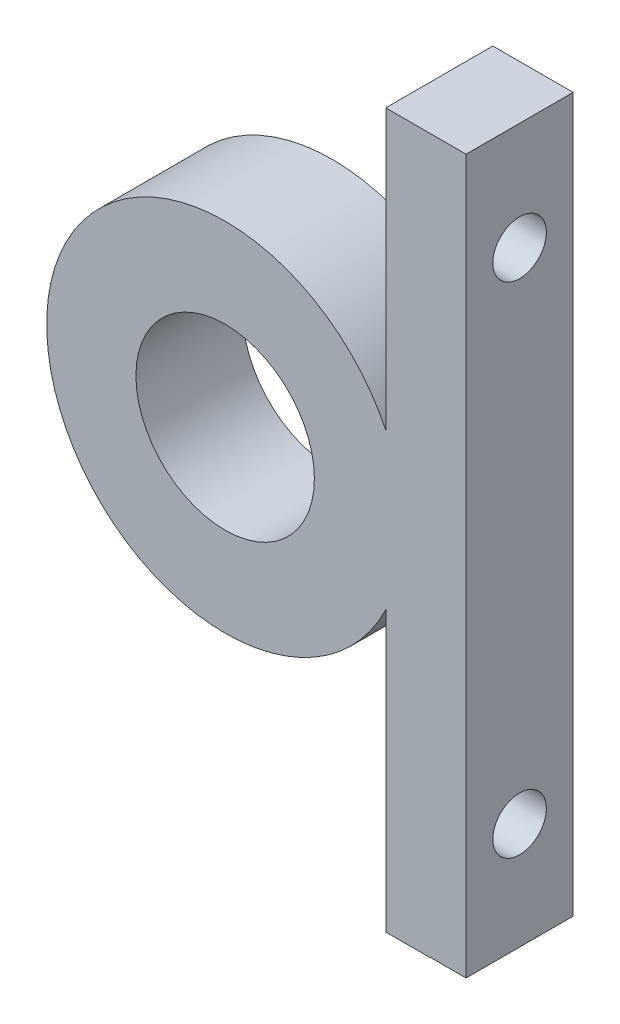
SolidWorks part; units mm, degrees
ref_plane "Front Plane" through (0, 0, 0) normal (0, 0, 1) x (1, 0, 0)
ref_plane "Top Plane" through (0, 0, 0) normal (0, 1, 0) x (1, 0, 0)
ref_plane "Right Plane" through (0, 0, 0) normal (1, 0, 0) x (0, 0, -1)
sketch "Sketch1" plane through (0, 0, 0) normal (0, 0, 1) x (1, 0, 0)
  line L0 (0, 22.784) -> (0, -28.016)
  line L1 (0, -28.016) -> (3.175, -28.016)
  line L2 (3.175, -28.016) -> (3.175, 22.784)
  line L3 (3.175, 22.784) -> (0, 22.784)
  line L4 (-11.43, -2.616) -> (3.175, -2.616) construction
  circle A0 centre (-11.43, -2.616) radius 12.7
  circle A1 centre (-11.43, -2.616) radius 6.35
  point P9 (3.175, -2.616)
  dimension "D2" = 12.7
  dimension "D3" = 25.4
  dimension "D1" = 3.175
  dimension "D4" = 14.605
  dimension "D5" = 50.8
  dimension "D6" = 25.4
extrude "Boss-Extrude1" add sketch "Sketch1" along normal blind 7.62 contours L0 A0 A1 | A0 L0 L1 L2 L3 | L0 A0 | L4 L0 A0 | L4 A0 L0 L1 L2
ref_plane "Plane1" through (5.715, 0, 0) normal (1, 0, 0) x (0, 0, -1)
sketch "Sketch3" plane through (5.715, 0, 0) normal (1, 0, 0) x (0, 0, -1)
  line L0 (-3.81, 22.784) -> (-3.81, -28.016) construction
  line L1 (-7.62, 22.784) -> (0, 22.784) construction
  line L2 (-7.62, -28.016) -> (0, -28.016) construction
  line L3 (-3.81, -28.016) -> (-3.81, -20.396)
  line L4 (-3.81, 22.784) -> (-3.81, 15.1167)
  circle A0 centre (-3.81, 15.1167) radius 1.905
  circle A1 centre (-3.81, -20.396) radius 1.905
  dimension "D1" = 3.81
  dimension "D2" = 3.81
extrude "Cut-Extrude1" cut sketch "Sketch3" against normal blind 10.16 and the other way blind 7.62 contours L0 L4 A0 | L4 L0 A0 | L0 A1 L3 | A1 L0 L3
sketch "Sketch4" plane through (0, 0, 7.62) normal (0, 0, 1) x (1, 0, 0)
  line L1 (3.175, 22.784) -> (5.715, 22.784)
  line L2 (3.175, 22.784) -> (3.175, -27.9921)
  line L3 (3.175, -27.9921) -> (5.715, -27.9921)
  line L4 (5.715, 22.784) -> (5.715, -27.9921)
  dimension "D1" = 2.54
extrude "Boss-Extrude2" add sketch "Sketch4" against normal blind 7.62
sketch "Sketch5" plane through (5.715, 0, 0) normal (1, 0, 0) x (0, 0, -1)
  circle A0 centre (-3.81, 15.1167) radius 1.905
  circle A1 centre (-3.81, -20.396) radius 1.905
extrude "Cut-Extrude2" cut sketch "Sketch5" against normal blind 7.62
